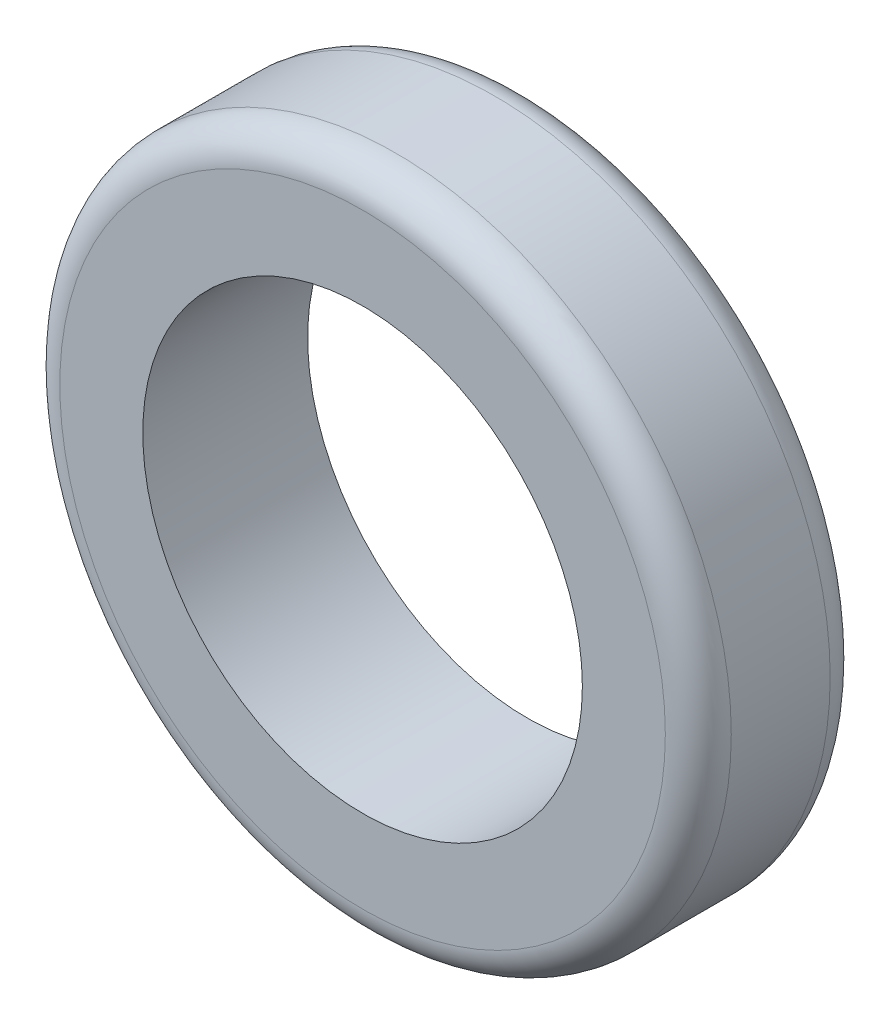
SolidWorks part; units mm, degrees
ref_plane "Plan de face" through (0, 0, 0) normal (0, 0, 1) x (1, 0, 0)
ref_plane "Plan de dessus" through (0, 0, 0) normal (0, 1, 0) x (1, 0, 0)
ref_plane "Plan de droite" through (0, 0, 0) normal (1, 0, 0) x (0, 0, -1)
sketch "Esquisse1" plane through (0, 0, 0) normal (0, 0, 1) x (1, 0, 0)
  circle A0 centre (0, 0) radius 30.55
  circle A2 centre (0, 0) radius 20
extrude "Boss.-Extru.1" add sketch "Esquisse1" along normal blind 15 contours A0
fillet "Congé1" radius 3 2 edges at (30.55, 0, 0) (30.55, 0, 15)
